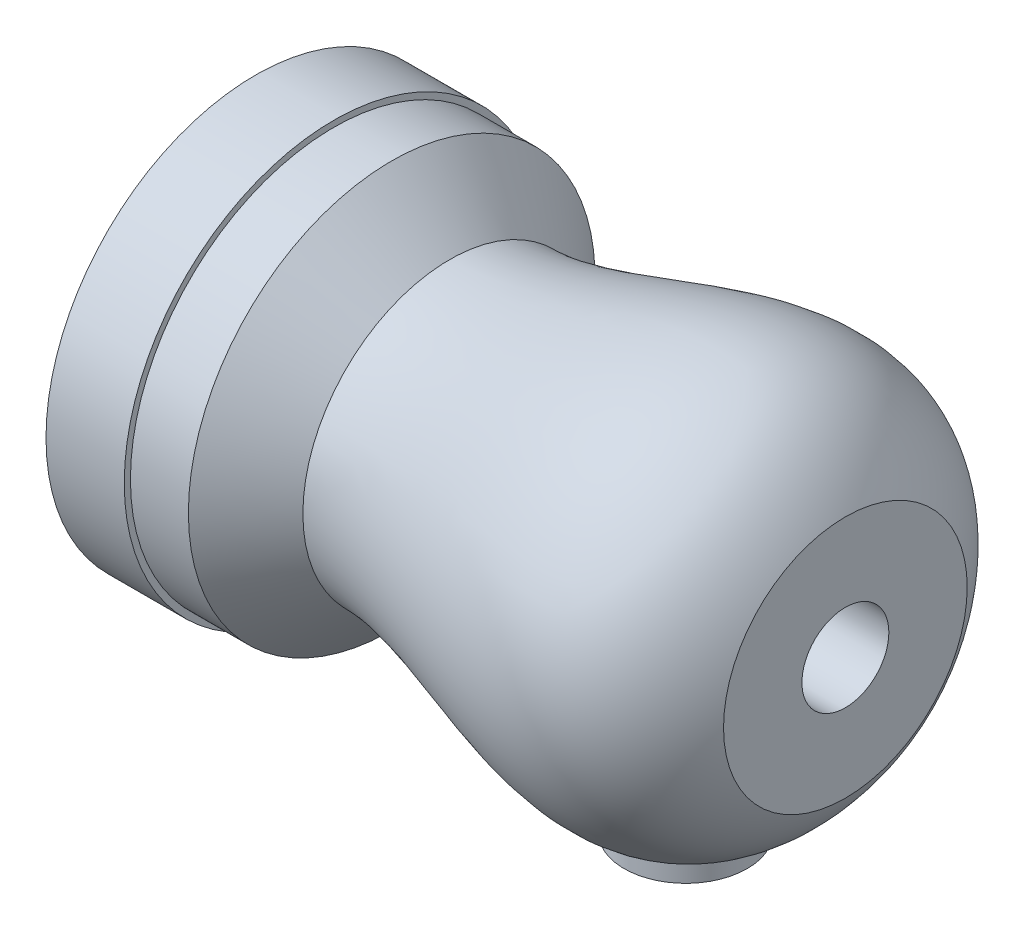
SolidWorks part; units mm, degrees
ref_plane "前基準面" through (0, 0, 0) normal (0, 0, 1) x (1, 0, 0)
ref_plane "上基準面" through (0, 0, 0) normal (0, 1, 0) x (1, 0, 0)
ref_plane "右基準面" through (0, 0, 0) normal (1, 0, 0) x (0, 0, -1)
sketch "草圖1" plane through (0, 0, 0) normal (0, 0, 1) x (1, 0, 0)
  line L0 (0, 0) -> (0, 70.1434)
  line L1 (0, 70.1434) -> (20, 70.1434)
  line L2 (20, 70.1434) -> (40, 50.6508)
  line L3 (0, 0) -> (176.4956, 0)
  line L4 (176.4956, 0) -> (176.4956, 42.0295)
  spline S0 degree 3 poles (40, 50.6508) (85.3897, 50.7333) (143.7053, 100.0034) (176.4956, 42.0295) knots 0 0 0 0 1 1 1 1
  dimension "D2" = 150
  dimension "D1" = 20
  dimension "D3" = 20
revolve "旋轉1" add sketch "草圖1" angle 360 about L3
sketch "草圖2" plane through (176.4956, 0, 0) normal (1, 0, 0) x (0, 0, -1)
  circle A0 centre (0, 0) radius 15
  dimension "D1" = 30
ref_plane "平面1" through (0, -70, 0) normal (0, 1, 0) x (1, 0, 0)
sketch "草圖3" plane through (0, -70, 0) normal (0, 1, 0) x (1, 0, 0)
  circle A0 centre (121.4013, 0) radius 11.25
  dimension "D1" = 22.5
extrude "伸長-薄件1" add sketch "草圖3" against normal blind 10 and the other way blind 33 thin
sketch "草圖4" plane through (0, 0, 0) normal (-1, 0, 0) x (0, 0, 1)
  circle A0 centre (0, 0) radius 72.265
extrude "填料-伸長1" add sketch "草圖4" along normal blind 27
extrude "除料-伸長1" cut sketch "草圖2" against normal blind 220
